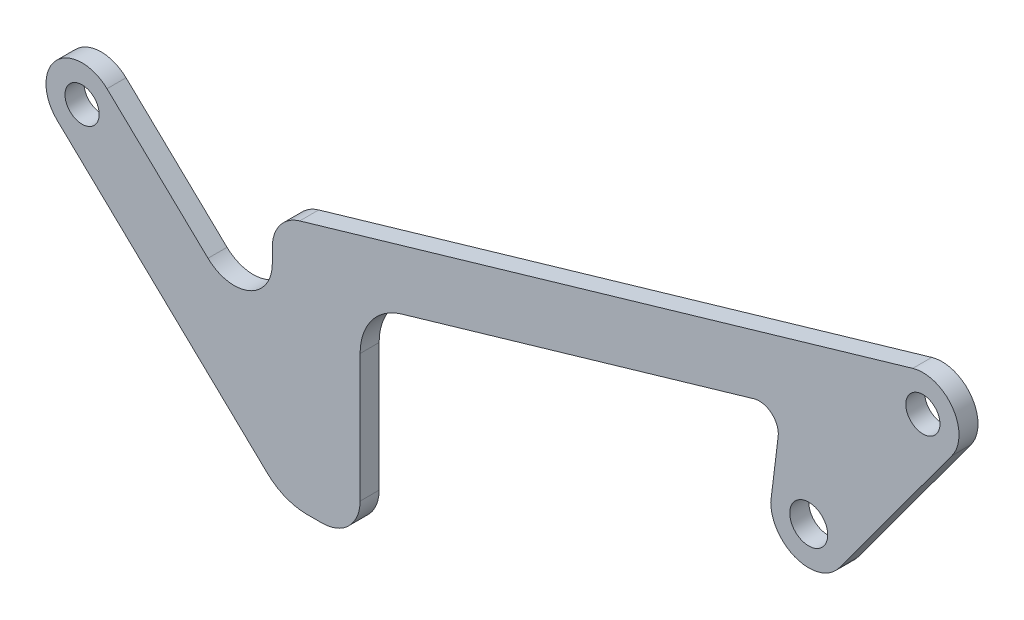
SolidWorks part; units mm, degrees
ref_plane "Front Plane" through (0, 0, 0) normal (0, 0, 1) x (1, 0, 0)
ref_plane "Top Plane" through (0, 0, 0) normal (0, 1, 0) x (1, 0, 0)
ref_plane "Right Plane" through (0, 0, 0) normal (1, 0, 0) x (0, 0, -1)
sketch "Sketch1" plane through (0, 0, 0) normal (0, 0, 1) x (1, 0, 0)
  line L11 (-191, 0) -> (1.1294, 0) construction
  line L13 (-133.8005, 2.1003) -> (27.3423, 49.1102)
  line L14 (-197.5506, -6.8666) -> (-142.2704, -59.6026)
  line L15 (-184.4494, 6.8666) -> (-157.9026, -18.4585)
  line L16 (-141, -7.4996) -> (-141, -11.2229)
  line L17 (37.6486, 34.3822) -> (8.0515, -5.9138)
  line L19 (-117.9237, -20.1426) -> (-117.9237, -53.7492)
  line L20 (-127.9237, -63.7492) -> (-131.9165, -63.7492)
  line L21 (-107.1246, -5.7428) -> (-14.398, 21.3082)
  line L22 (-8.0351, 15.898) -> (-9.99, 0)
  circle A0 centre (0, 0) radius 4.99
  circle A1 centre (-191, 0) radius 4.49
  circle A2 centre (30, 40) radius 4.49
  arc A15 (-184.4494, 6.8666) -> (-197.5506, -6.8666) centre (-191, 0) ccw
  arc A16 (-9.99, 0) -> (8.0515, -5.9138) centre (0, 0) ccw
  arc A17 (37.6486, 34.3822) -> (27.3423, 49.1102) centre (30, 40) ccw
  arc A18 (-141, -11.2229) -> (-157.9026, -18.4585) centre (-151, -11.2229) cw
  arc A19 (-131.9165, -63.7492) -> (-142.2704, -59.6026) centre (-131.9165, -48.7492) cw
  arc A20 (-127.9237, -63.7492) -> (-117.9237, -53.7492) centre (-127.9237, -53.7492) ccw
  arc A21 (-133.8005, 2.1003) -> (-141, -7.4996) centre (-131, -7.4996) ccw
  arc A23 (-8.0351, 15.898) -> (-14.398, 21.3082) centre (-12.9977, 16.5082) ccw
  arc A24 (-117.9237, -20.1426) -> (-107.1246, -5.7428) centre (-102.9237, -20.1426) cw
  point P17 (39.49, 120)
  point P26 (-137.9237, -63.7492)
  point P29 (-117.9237, -63.7492)
  point P32 (-141, 0)
  dimension "D1" = 8.98
  dimension "D2" = 9.98
  dimension "D3" = 8.98
  dimension "D6" = 5
  dimension "D7" = 5
  dimension "D8" = 5
  dimension "D10" = 20
  dimension "D11" = 50
  dimension "D12" = 10
  dimension "D13" = 15
  dimension "D14" = 10
  dimension "D15" = 10
  dimension "D16" = 15
  dimension "D17" = 5
  dimension "D18" = 15
  dimension "D4" = 191
  dimension "D5" = 40
  dimension "D9" = 50
extrude "Boss-Extrude1" add sketch "Sketch1" along normal blind 5
ref_plane "Plane1" through (0, 0, -0.5) normal (0, 0, 1) x (1, 0, 0)
sketch "Sketch2" plane through (0, 0, 5) normal (0, 0, 1) x (1, 0, 0)
  line L0 (-191, 0) -> (0, 0) construction
